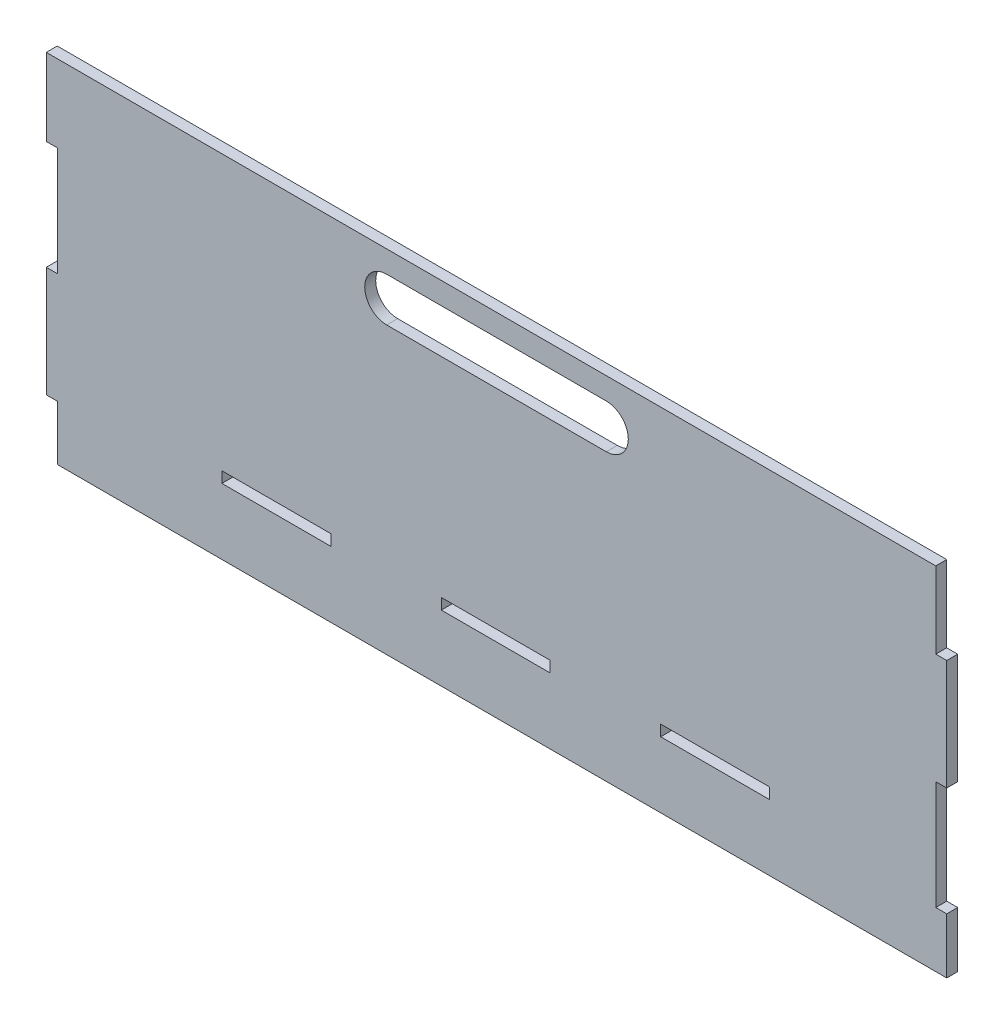
SolidWorks part; units mm, degrees
ref_plane "Ebene vorne" through (0, 0, 0) normal (0, 0, 1) x (1, 0, 0)
ref_plane "Ebene oben" through (0, 0, 0) normal (0, 1, 0) x (1, 0, 0)
ref_plane "Ebene rechts" through (0, 0, 0) normal (1, 0, 0) x (0, 0, -1)
sketch "Skizze1" plane through (0, 0, 0) normal (0, 0, 1) x (1, 0, 0)
  line L1 (0, 0) -> (410, 0)
  line L2 (0, 0) -> (0, 300)
  line L3 (0, 300) -> (410, 300)
  line L4 (410, 0) -> (410, 300)
  dimension "D1" = 410
  dimension "D2" = 300
extrude "Aufsatz-Linear austragen1" add sketch "Skizze1" along normal blind 5
sketch "Skizze2" plane through (0, 0, 5) normal (0, 0, 1) x (1, 0, 0)
  line L0 (410, 300) -> (0, 300) construction
  line L1 (-41.676, 324.65) -> (5, 324.65)
  line L2 (-41.676, 324.65) -> (-41.676, 275.05)
  line L3 (-41.676, 275.05) -> (5, 275.05)
  line L4 (5, 324.65) -> (5, 275.05)
  dimension "D1" = 49.6
  dimension "D3" = 5
  dimension "D4" = 24.95
extrude "Schnitt-Linear austragen1" cut sketch "Skizze2" against normal blind 5
pattern_linear "Lineares Muster1" count 4 spacing 99.9 along (0, -1, 0) of "Schnitt-Linear austragen1"
ref_plane "Ebene1" through (0, 150, 0) normal (0, 1, 0) x (1, 0, 0)
sketch "Skizze3" plane through (0, 0, 5) normal (0, 0, 1) x (1, 0, 0)
  line L1 (405, 274.7) -> (432.6636, 274.7)
  line L2 (405, 274.7) -> (405, 225.1)
  line L3 (405, 225.1) -> (432.6636, 225.1)
  line L4 (432.6636, 274.7) -> (432.6636, 225.1)
  dimension "D1" = 49.6
  dimension "D2" = 5
  dimension "D3" = 25.3
extrude "Schnitt-Linear austragen2" cut sketch "Skizze3" against normal blind 5
pattern_linear "Lineares Muster2" count 3 spacing 99.9 along (0, -1, 0) of "Schnitt-Linear austragen2"
sketch "Skizze4" plane through (0, 0, 5) normal (0, 0, 1) x (1, 0, 0)
  line L1 (0, 75.25) -> (0, 24.95) construction
  line L2 (79.95, 35) -> (129.55, 35)
  line L3 (79.95, 35) -> (79.95, 30)
  line L4 (79.95, 30) -> (129.55, 30)
  line L5 (129.55, 35) -> (129.55, 30)
  line L6 (5, 0) -> (410, 0) construction
  dimension "D1" = 79.95
  dimension "D2" = 5
  dimension "D3" = 49.6
  dimension "D4" = 30
extrude "Schnitt-Linear austragen3" cut sketch "Skizze4" against normal blind 5
pattern_linear "Lineares Muster3" count 3 spacing 99.9 along (1, 0, 0) of "Schnitt-Linear austragen3"
sketch "Skizze5" plane through (0, 0, 5) normal (0, 0, 1) x (1, 0, 0)
  line L0 (0, 160) -> (405, 160)
  line L1 (410, 74.9) -> (410, 125.2) construction
  line L2 (0, 175.15) -> (0, 124.85) construction
  line L3 (405, 174.8) -> (405, 125.2) construction
  line L4 (5, 0) -> (410, 0) construction
  line L5 (0, 160) -> (-27.8258, 200.4922)
  line L8 (-27.8258, 200.4922) -> (-27.8258, 333.8243)
  line L9 (-27.8258, 333.8243) -> (496.6631, 346.3375)
  line L10 (496.6631, 346.3375) -> (405, 160)
  line L11 (155, 140) -> (255, 140) construction
  line L12 (155, 150) -> (255, 150)
  line L13 (155, 130) -> (255, 130)
  arc A0 (155, 150) -> (155, 130) centre (155, 140) ccw
  arc A1 (255, 130) -> (255, 150) centre (255, 140) ccw
  point P13 (205, 140)
  dimension "D2" = 10
  dimension "D1" = 160
  dimension "D3" = 10
  dimension "D4" = 100
  dimension "D5" = 155
  dimension "D6" = 155
extrude "Schnitt-Linear austragen4" cut sketch "Skizze5" against normal blind 5
